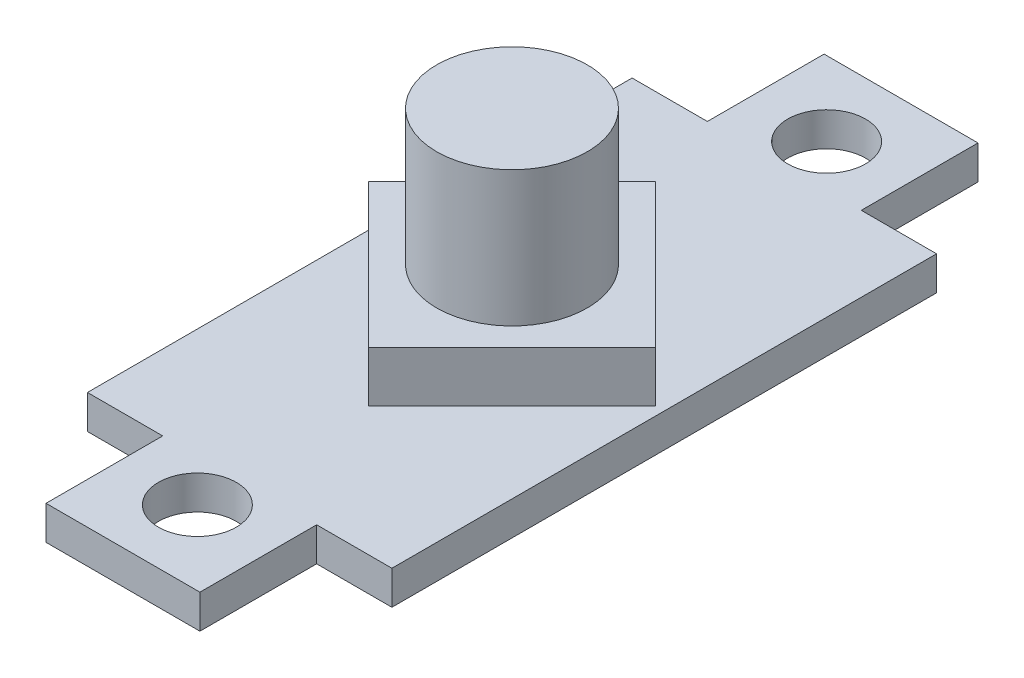
SolidWorks part; units mm, degrees
ref_plane "Front Plane" through (0, 0, 0) normal (0, 0, 1) x (1, 0, 0)
ref_plane "Top Plane" through (0, 0, 0) normal (0, 1, 0) x (1, 0, 0)
ref_plane "Right Plane" through (0, 0, 0) normal (1, 0, 0) x (0, 0, -1)
sketch "Sketch1" plane through (0, 0, 0) normal (0, 1, 0) x (1, 0, 0)
  line L0 (0, 11.5) -> (0, -11.5) construction
  line L1 (-4.5, 11.5) -> (4.5, 11.5)
  line L2 (-4.5, 11.5) -> (-4.5, -11.5)
  line L3 (-4.5, -11.5) -> (4.5, -11.5)
  line L4 (4.5, 11.5) -> (4.5, -11.5)
  line L5 (-4.5, 11.5) -> (4.5, -11.5) construction
  line L6 (-4.5, -11.5) -> (4.5, 11.5) construction
  line L7 (-2.275, 11.5) -> (2.275, 11.5)
  line L8 (-2.275, 11.5) -> (-2.275, -11.5)
  line L9 (-2.275, -11.5) -> (2.275, -11.5)
  line L10 (2.275, 11.5) -> (2.275, -11.5)
  line L11 (-2.275, 11.5) -> (2.275, -11.5) construction
  line L12 (-2.275, -11.5) -> (2.275, 11.5) construction
  line L13 (4.5, 8.05) -> (-4.5, 8.05)
  line L14 (4.5, 8.05) -> (4.5, -8.05)
  line L15 (4.5, -8.05) -> (-4.5, -8.05)
  line L16 (-4.5, 8.05) -> (-4.5, -8.05)
  line L17 (4.5, 8.05) -> (-4.5, -8.05) construction
  line L18 (4.5, -8.05) -> (-4.5, 8.05) construction
  line L19 (-4.5, 0) -> (4.5, 0) construction
  circle A0 centre (0, 9.3) radius 1.15
  circle A1 centre (0, -9.3) radius 1.15
  point P0 (0, 0)
  point P6 (0, 0)
  point P11 (0, 0)
  dimension "D6" = 2.3
  dimension "D1" = 9
  dimension "D2" = 23
  dimension "D3" = 4.55
  dimension "D4" = 16.1
  dimension "D5" = 18.6
extrude "Boss-Extrude1" add sketch "Sketch1" along normal blind 1 contours L15 L8 L13 L2 | L13 L10 L1 L8 A0 | L15 L10 L13 L8 | L15 L4 L13 L10 | L10 L15 L8 L3 A1
sketch "Sketch2" plane through (0, 1, 0) normal (0, 1, 0) x (1, 0, 0)
  line L0 (0, 11.5) -> (0, -11.5) construction
  line L1 (0, -4.2426) -> (4.2426, 0)
  line L2 (4.2426, 0) -> (0, 4.2426)
  line L3 (0, 4.2426) -> (-4.2426, 0)
  line L4 (-4.2426, 0) -> (0, -4.2426)
  line L5 (-2.275, 11.5) -> (2.275, 11.5) construction
  line L6 (-2.275, -11.5) -> (2.275, -11.5) construction
  circle A0 centre (0, 0) radius 3 construction
  dimension "D1" = 6
extrude "Boss-Extrude2" add sketch "Sketch2" along normal blind 1.5
sketch "Sketch3" plane through (0, 2.5, 0) normal (0, 1, 0) x (1, 0, 0)
  circle A0 centre (0, 0) radius 2.2266
extrude "Boss-Extrude3" add sketch "Sketch3" along normal blind 4
